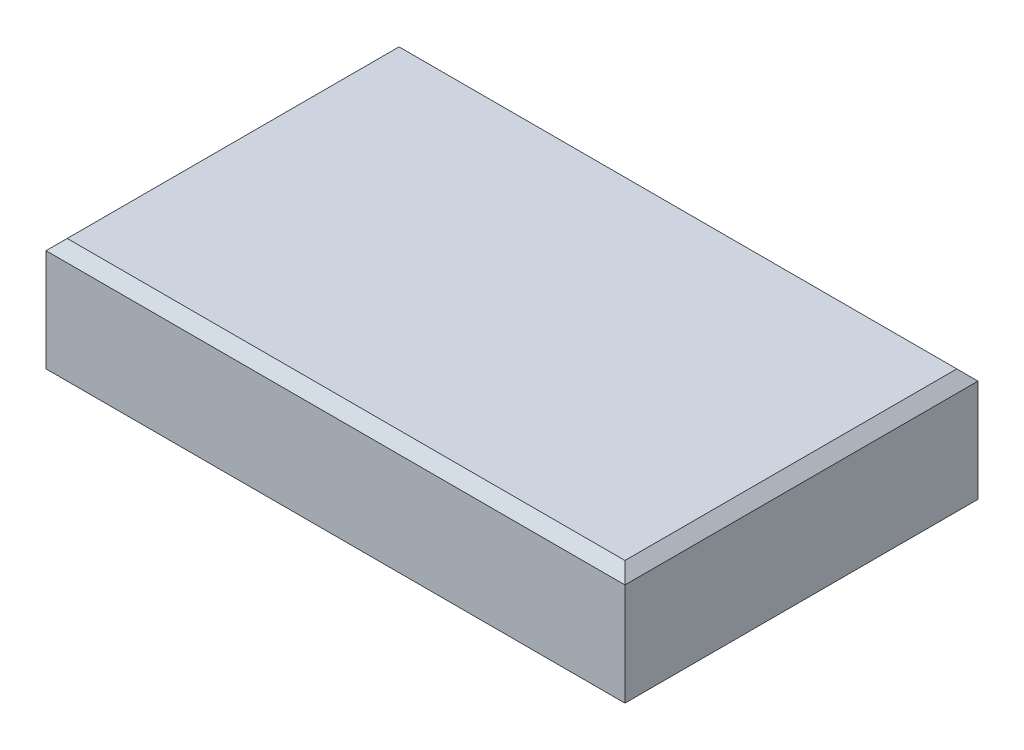
SolidWorks part; units mm, degrees
ref_plane "Front Plane" through (0, 0, 0) normal (0, 0, 1) x (1, 0, 0)
ref_plane "Top Plane" through (0, 0, 0) normal (0, 1, 0) x (1, 0, 0)
ref_plane "Right Plane" through (0, 0, 0) normal (1, 0, 0) x (0, 0, -1)
sketch "Sketch1" plane through (0, 0, 0) normal (0, 1, 0) x (1, 0, 0)
  line L1 (-41, -25) -> (41, -25)
  line L2 (-41, -25) -> (-41, 25)
  line L3 (-41, 25) -> (41, 25)
  line L4 (41, -25) -> (41, 25)
  line L5 (-41, -25) -> (41, 25) construction
  line L6 (-41, 25) -> (41, -25) construction
  point P0 (0, 0)
  dimension "D1" = 50
  dimension "D2" = 82
extrude "Boss-Extrude1" add sketch "Sketch1" along normal mid plane 16
chamfer "Chamfer1" distance 1.5 angle 45 4 edges at (41, 8, 0) (0, 8, -25) (-41, 8, 0) (0, 8, 25)
